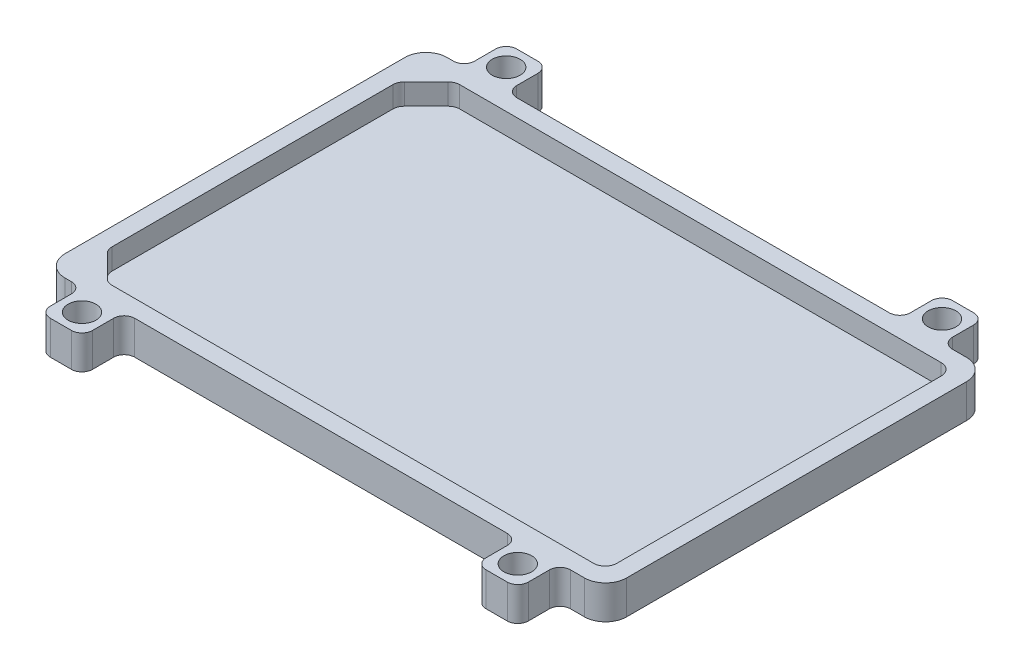
SolidWorks part; units mm, degrees
ref_plane "Front Plane" through (0, 0, 0) normal (0, 0, 1) x (1, 0, 0)
ref_plane "Top Plane" through (0, 0, 0) normal (0, 1, 0) x (1, 0, 0)
ref_plane "Right Plane" through (0, 0, 0) normal (1, 0, 0) x (0, 0, -1)
sketch "Sketch1" plane through (0, 0, 0) normal (0, 1, 0) x (1, 0, 0)
  line L1 (0, 0) -> (157.864, 0)
  line L2 (0, 0) -> (0, -90.551)
  line L3 (0, -90.551) -> (157.864, -90.551)
  line L4 (157.864, 0) -> (157.864, -90.551)
  dimension "D1" = 157.864
  dimension "D2" = 90.551
extrude "Boss-Extrude1" add sketch "Sketch1" along normal blind 8
sketch "Sketch7" plane through (0, 0, 0) normal (0, -1, 0) x (1, 0, 0)
  circle A0 centre (33.602, 72.2755) radius 8.95
  circle A1 centre (33.602, 18.2755) radius 8.5
  circle A2 centre (51.692, 72.2755) radius 8.95
  circle A3 centre (69.782, 72.2755) radius 8.95
  circle A4 centre (87.872, 72.2755) radius 8.95
  circle A5 centre (105.962, 72.2755) radius 8.95
  circle A6 centre (124.052, 72.2755) radius 8.95
  circle A7 centre (51.692, 54.2755) radius 8.95
  circle A8 centre (69.782, 54.2755) radius 8.95
  circle A9 centre (87.872, 54.2755) radius 8.95
  circle A10 centre (105.962, 54.2755) radius 8.95
  circle A11 centre (124.052, 54.2755) radius 8.95
  circle A12 centre (51.692, 36.2755) radius 8.95
  circle A13 centre (69.782, 36.2755) radius 8.95
  circle A14 centre (87.872, 36.2755) radius 8.95
  circle A15 centre (105.962, 36.2755) radius 8.95
  circle A16 centre (124.052, 36.2755) radius 8.95
  circle A17 centre (51.692, 18.2755) radius 8.95
  circle A18 centre (69.782, 18.2755) radius 8.95
  circle A19 centre (87.872, 18.2755) radius 8.95
  circle A20 centre (105.962, 18.2755) radius 8.95
  circle A21 centre (124.052, 18.2755) radius 8.95
  circle A22 centre (33.602, 54.2755) radius 8.95
  circle A23 centre (33.602, 36.2755) radius 8.95
  circle A24 centre (33.602, 18.2755) radius 8.95
  circle A25 centre (51.692, 18.2755) radius 8.5
  circle A26 centre (69.782, 18.2755) radius 8.5
  circle A27 centre (87.872, 18.2755) radius 8.5
  circle A28 centre (105.962, 18.2755) radius 8.5
  circle A29 centre (124.052, 18.2755) radius 8.5
  circle A30 centre (33.602, 36.2755) radius 8.5
  circle A31 centre (51.692, 36.2755) radius 8.5
  circle A32 centre (69.782, 36.2755) radius 8.5
  circle A33 centre (87.872, 36.2755) radius 8.5
  circle A34 centre (105.962, 36.2755) radius 8.5
  circle A35 centre (124.052, 36.2755) radius 8.5
  circle A36 centre (33.602, 54.2755) radius 8.5
  circle A37 centre (51.692, 54.2755) radius 8.5
  circle A38 centre (69.782, 54.2755) radius 8.5
  circle A39 centre (87.872, 54.2755) radius 8.5
  circle A40 centre (105.962, 54.2755) radius 8.5
  circle A41 centre (124.052, 54.2755) radius 8.5
  circle A42 centre (124.052, 72.2755) radius 8.5
  circle A43 centre (105.962, 72.2755) radius 8.5
  circle A44 centre (87.872, 72.2755) radius 8.5
  circle A45 centre (69.782, 72.2755) radius 8.5
  circle A46 centre (51.692, 72.2755) radius 8.5
  circle A47 centre (33.602, 72.2755) radius 8.5
  dimension "D1" = 17.9
  dimension "D2" = 17
  dimension "D6" = 18
  dimension "D3" = 18.09
  dimension "D4" = 18
  dimension "D5" = 18.09
  dimension "D7" = 6
  dimension "D8" = 4
sketch "Sketch23" plane through (0, 8, 0) normal (0, 1, 0) x (1, 0, 0)
  line L1 (141.332, -86.4755) -> (23.3181, -86.4755)
  line L2 (141.332, -86.4755) -> (141.332, -4.0755)
  line L3 (141.332, -4.0755) -> (23.3181, -4.0755)
  line L4 (16.532, -79.6894) -> (16.532, -10.8616)
  line L5 (16.532, -10.8616) -> (23.3181, -4.0755)
  line L6 (23.3181, -4.0755) -> (16.532, -4.0755) construction
  line L7 (16.532, -4.0755) -> (16.532, -10.8616) construction
  line L8 (23.3181, -86.4755) -> (16.532, -79.6894)
  line L10 (157.864, 0) -> (0, 0) construction
  line L11 (141.332, -4.0755) -> (141.332, 0) construction
  line L12 (23.3181, -86.4755) -> (16.532, -86.4755) construction
  line L13 (16.532, -86.4755) -> (16.532, -79.6894) construction
  line L14 (157.864, -90.551) -> (157.864, 0) construction
  line L15 (141.332, -86.4755) -> (157.864, -86.4755) construction
  line L16 (16.532, -86.4755) -> (0, -86.4755) construction
  line L17 (0, 0) -> (0, -90.551) construction
  line L18 (157.864, 0) -> (0, 0) construction
  line L19 (141.332, -86.4755) -> (141.332, -90.551) construction
  line L20 (0, -90.551) -> (157.864, -90.551) construction
  dimension "D2" = 124.8
  dimension "D3" = 9.597
  dimension "D5" = 9.597
  dimension "D9" = 82.4
  dimension "D10" = 4.0755
extrude "Cut-Extrude21" cut sketch "Sketch23" against normal blind 5
fillet "Fillet8" radius 2.75 6 edges at (141.332, 5.5, 4.0755) (16.532, 5.5, 10.8616) (23.3181, 5.5, 4.0755) (141.332, 5.5, 86.4755) (23.3181, 5.5, 86.4755) (16.532, 5.5, 79.6894)
sketch "Sketch29" plane through (0, 8, 0) normal (0, 1, 0) x (1, 0, 0)
  line L0 (157.864, 0) -> (0, 0) construction
  line L1 (157.864, -90.551) -> (145.4887, -90.551)
  line L2 (157.864, -90.551) -> (157.864, 0)
  line L3 (157.864, 0) -> (145.4887, 0)
  line L4 (145.4887, -90.551) -> (145.4887, 0)
  line L6 (0, -90.551) -> (12.3753, -90.551)
  line L7 (0, -90.551) -> (0, 0)
  line L8 (0, 0) -> (12.3753, 0)
  line L9 (12.3753, -90.551) -> (12.3753, 0)
  dimension "D2" = 4.0755
extrude "Cut-Extrude25" cut sketch "Sketch29" against normal through all
fillet "Fillet9" radius 5 4 edges at (145.4887, 4, 90.551) (145.4887, 4, 0) (12.3753, 4, 90.551) (12.3753, 4, 0)
sketch "Sketch36" plane through (0, 0, 0) normal (0, -1, 0) x (1, 0, 0)
  line L0 (17.3753, 90.551) -> (140.4887, 90.551) construction
  line L1 (21.3936, 90.551) -> (31.3936, 90.551)
  line L2 (21.3936, 90.551) -> (21.3936, 100.551)
  line L3 (21.3936, 100.551) -> (31.3936, 100.551)
  line L4 (31.3936, 90.551) -> (31.3936, 100.551)
  line L5 (140.4887, 0) -> (17.3753, 0) construction
  line L6 (124.6936, 90.551) -> (134.6936, 90.551)
  line L7 (124.6936, 90.551) -> (124.6936, 100.551)
  line L8 (124.6936, 100.551) -> (134.6936, 100.551)
  line L9 (134.6936, 90.551) -> (134.6936, 100.551)
  line L10 (31.3936, 0) -> (21.3936, 0)
  line L11 (31.3936, 0) -> (31.3936, -10)
  line L12 (31.3936, -10) -> (21.3936, -10)
  line L13 (21.3936, 0) -> (21.3936, -10)
  line L15 (124.6936, 0) -> (134.6936, 0)
  line L16 (124.6936, 0) -> (124.6936, -10)
  line L17 (124.6936, -10) -> (134.6936, -10)
  line L18 (134.6936, 0) -> (134.6936, -10)
  line L22 (134.6936, 90.551) -> (124.6936, 100.551) construction
  line L23 (124.6936, 90.551) -> (134.6936, 100.551) construction
  line L24 (31.3936, 100.551) -> (21.3936, 90.551) construction
  line L25 (31.3936, 90.551) -> (21.3936, 100.551) construction
  line L26 (21.3936, 0) -> (31.3936, -10) construction
  line L27 (31.3936, 0) -> (21.3936, -10) construction
  line L28 (21.3936, -10) -> (21.4692, -10.0262) construction
  line L29 (134.6936, 0) -> (124.6936, -10) construction
  line L30 (134.6936, -10) -> (124.6936, 0) construction
  circle A0 centre (129.6936, -5) radius 3.3
  circle A1 centre (26.3936, -5) radius 3.3
  circle A2 centre (26.3936, 95.551) radius 3.3
  circle A3 centre (129.6936, 95.551) radius 3.3
  dimension "D5" = 6.6
  dimension "D9" = 6.6
  dimension "D10" = 5.7951
  dimension "D1" = 93.3
  dimension "D2" = 93.3
  dimension "D3" = 10
  dimension "D4" = 10
  dimension "D6" = 4.0183
  dimension "D7" = 4.0183
  dimension "D8" = 5.7951
extrude "Boss-Extrude10" add sketch "Sketch36" against normal up to surface (8 mm away) up to face at (78.932, 8, 45.2755)
fillet "Fillet10" radius 2.5 16 edges at (21.3936, 4, 100.551) (31.3936, 4, 100.551) (124.6936, 4, 100.551) (134.6936, 4, 100.551) (134.6936, 4, -10) (124.6936, 4, -10) (31.3936, 4, -10) (21.3936, 4, -10) (124.6936, 4, 90.551) (21.3936, 4, 90.551) (134.6936, 4, 90.551) (31.3936, 4, 90.551) (134.6936, 4, 0) (124.6936, 4, 0) (31.3936, 4, 0) (21.3936, 4, 0)
